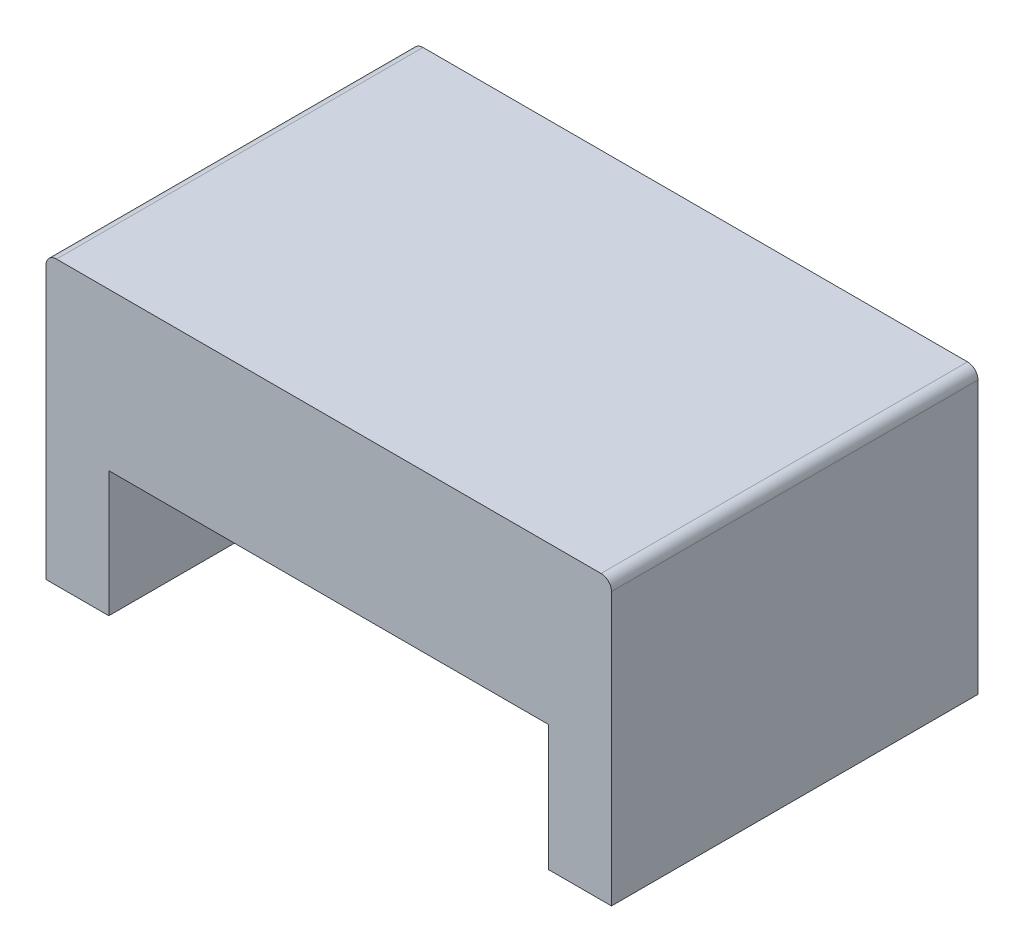
SolidWorks part; units mm, degrees
ref_plane "Front Plane" through (0, 0, 0) normal (0, 0, 1) x (1, 0, 0)
ref_plane "Top Plane" through (0, 0, 0) normal (0, 1, 0) x (1, 0, 0)
ref_plane "Right Plane" through (0, 0, 0) normal (1, 0, 0) x (0, 0, -1)
sketch "Sketch1" plane through (0, 0, 0) normal (0, 0, 1) x (1, 0, 0)
  line L0 (-25.3408, -16.8813) -> (-25.3408, -4.8813)
  line L1 (-25.3408, -4.8813) -> (16.6592, -4.8813)
  line L2 (16.6592, -4.8813) -> (16.6592, -16.8813)
  line L3 (16.6592, -16.8813) -> (22.6592, -16.8813)
  line L4 (22.6592, -16.8813) -> (22.6592, 10.1187)
  line L5 (22.6592, 10.1187) -> (-31.3408, 10.1187)
  line L6 (-31.3408, 10.1187) -> (-31.3408, -16.8813)
  line L7 (-31.3408, -16.8813) -> (-25.3408, -16.8813)
  dimension "D1" = 42
  dimension "D2" = 6
  dimension "D3" = 15
  dimension "D4" = 12
extrude "Boss-Extrude1" add sketch "Sketch1" along normal blind 35
fillet "Fillet1" radius 1 2 edges at (22.6592, 10.1187, 17.5) (-31.3408, 10.1187, 17.5)
